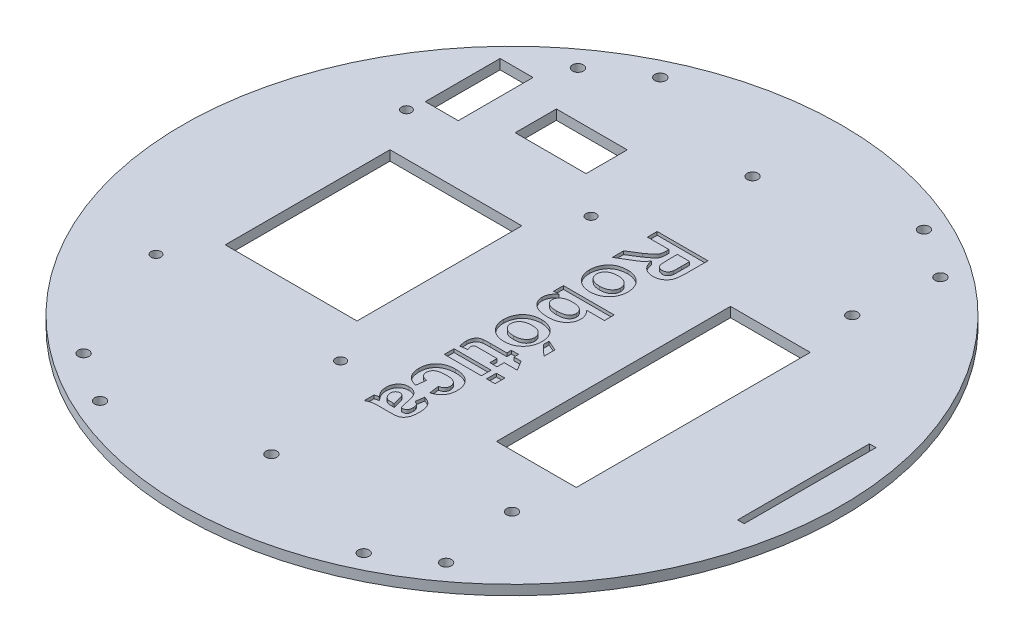
SolidWorks part; units mm, degrees
ref_plane "Alzado" through (0, 0, 0) normal (0, 0, 1) x (1, 0, 0)
ref_plane "Planta" through (0, 0, 0) normal (0, 1, 0) x (1, 0, 0)
ref_plane "Vista lateral" through (0, 0, 0) normal (1, 0, 0) x (0, 0, -1)
sketch "Croquis1" plane through (0, 0, 0) normal (0, 1, 0) x (1, 0, 0)
  line L0 (0, 71.35) -> (0, -71.35) construction
  line L5 (0, 0) -> (54.5026, 0) construction
  line L7 (30.8, 35.5) -> (55, 35.5)
  line L8 (30.8, 35.5) -> (30.8, -35.5)
  line L9 (30.8, -35.5) -> (55, -35.5)
  line L10 (55, 35.5) -> (55, -35.5)
  line L12 (-69.2993, 65.6851) -> (-59.2993, 65.6851)
  line L13 (-69.2993, 65.6851) -> (-69.2993, 42.9851)
  line L14 (-69.2993, 42.9851) -> (-59.2993, 42.9851)
  line L15 (-59.2993, 65.6851) -> (-59.2993, 42.9851)
  line L17 (-72.0203, 40) -> (-12.0203, 40) construction
  line L18 (-72.0203, 40) -> (-72.0203, -40) construction
  line L19 (-72.0203, -40) -> (-12.0203, -40) construction
  line L20 (-12.0203, 40) -> (-12.0203, -40) construction
  line L22 (-47.4922, 60.9632) -> (-25.9922, 60.9632)
  line L23 (-47.4922, 60.9632) -> (-47.4922, 48.4632)
  line L24 (-47.4922, 48.4632) -> (-25.9922, 48.4632)
  line L25 (-25.9922, 60.9632) -> (-25.9922, 48.4632)
  line L27 (-7, -66) -> (7, -66) construction
  line L28 (-7, -66) -> (-7, -97) construction
  line L29 (-7, -97) -> (7, -97) construction
  line L30 (7, -66) -> (7, -97) construction
  line L31 (41.7193, -51.6188) -> (51.6188, -41.7193) construction
  line L32 (41.7193, -51.6188) -> (63.6396, -73.5391) construction
  line L33 (63.6396, -73.5391) -> (73.5391, -63.6396) construction
  line L34 (51.6188, -41.7193) -> (73.5391, -63.6396) construction
  line L35 (66, -7) -> (66, 7) construction
  line L36 (66, -7) -> (97, -7) construction
  line L37 (97, -7) -> (97, 7) construction
  line L38 (66, 7) -> (97, 7) construction
  line L39 (51.6188, 41.7193) -> (41.7193, 51.6188) construction
  line L40 (51.6188, 41.7193) -> (73.5391, 63.6396) construction
  line L41 (73.5391, 63.6396) -> (63.6396, 73.5391) construction
  line L42 (41.7193, 51.6188) -> (63.6396, 73.5391) construction
  line L43 (7, 66) -> (-7, 66) construction
  line L44 (7, 66) -> (7, 97) construction
  line L45 (7, 97) -> (-7, 97) construction
  line L46 (-7, 66) -> (-7, 97) construction
  line L47 (0, 0) -> (-45.7335, 0) construction
  line L49 (-62.0203, 25) -> (-22.0203, 25)
  line L50 (-62.0203, 25) -> (-62.0203, -25)
  line L51 (-62.0203, -25) -> (-22.0203, -25)
  line L52 (-22.0203, 25) -> (-22.0203, -25)
  line L53 (88, 20.4593) -> (90, 20.4593)
  line L54 (88, 20.4593) -> (88, -19.5407)
  line L55 (88, -19.5407) -> (90, -19.5407)
  line L56 (90, 20.4593) -> (90, -19.5407)
  circle A6 centre (55, 75) radius 1.65
  circle A8 centre (55, -75) radius 1.65
  circle A10 centre (0, -73) radius 1.65
  circle A11 centre (51.6188, -51.6188) radius 1.65
  circle A13 centre (51.6188, 51.6188) radius 1.65
  circle A14 centre (0, 73) radius 1.65
  circle A15 centre (40, -85) radius 1.65
  circle A16 centre (40, 85) radius 1.65
  circle A19 centre (0, 0) radius 100
  circle A20 centre (73, 0) radius 1.65 [skipped]
  circle A21 centre (-70.0203, 38) radius 1.5
  circle A22 centre (-14.0203, 38) radius 1.5
  circle A23 centre (-14.0203, -38) radius 1.5
  circle A24 centre (-70.0203, -38) radius 1.5
  circle A25 centre (-40, -85) radius 1.65
  circle A26 centre (-55, -75) radius 1.65
  circle A27 centre (-55, 75) radius 1.65
  circle A28 centre (-40, 85) radius 1.65
  point P17 (0, 0)
  point P72 (0, 0)
  dimension "D10" = 200
  dimension "D14" = 3.3
  dimension "D3" = 3.3
  dimension "D7" = 3.3
  dimension "D27" = 3
  dimension "D28" = 3
  dimension "D2" = 73
  dimension "D4" = 5
  dimension "D5" = 75
  dimension "D6" = 55
  dimension "D8" = 40
  dimension "D9" = 85
  dimension "D11" = 71
  dimension "D12" = 24.2
  dimension "D13" = 35.5
  dimension "D15" = 22.7
  dimension "D16" = 10
  dimension "D17" = 80
  dimension "D18" = 60
  dimension "D19" = 40
  dimension "D20" = 21.5
  dimension "D21" = 12.5
  dimension "D22" = 14
  dimension "D23" = 7
  dimension "D24" = 31
  dimension "D25" = 7
  dimension "D29" = 2
  dimension "D30" = 2
  dimension "D31" = 2
  dimension "D32" = 2
  dimension "D33" = 50
  dimension "D34" = 40
  dimension "D35" = 10
  dimension "D36" = 40
  dimension "D37" = 2
  dimension "D38" = 90
  dimension "D26" = 5
extrude "Saliente-Extruir1" add sketch "Croquis1" along normal blind 3
sketch "Croquis2" plane through (0, 3, 0) normal (0, 1, 0) x (1, 0, 0)
  line L0 (0, 50) -> (0, -50) construction
  text T0 "Robótica" height in points 60
  point P3 (0, 0)
  dimension "D1" = 100
  dimension "D2" = 50
extrude "Cortar-Extruir1" cut sketch "Croquis2" against normal blind 1
